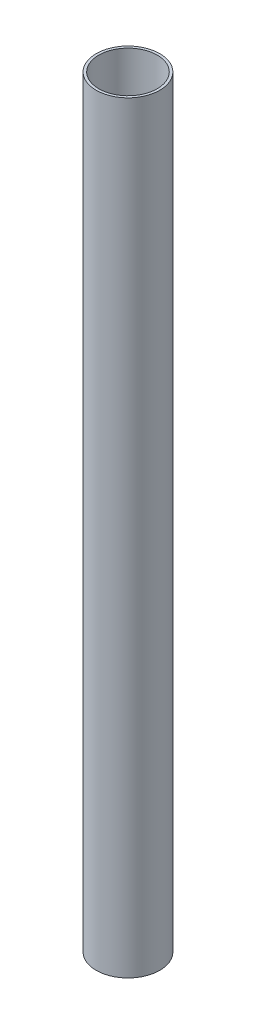
SolidWorks part; units mm, degrees
material "6061-T6 (SS)"
ref_plane "Front Plane" through (0, 0, 0) normal (0, 0, 1) x (1, 0, 0)
ref_plane "Top Plane" through (0, 0, 0) normal (0, 1, 0) x (1, 0, 0)
ref_plane "Right Plane" through (0, 0, 0) normal (1, 0, 0) x (0, 0, -1)
sketch "Sketch1" plane through (0, 0, 0) normal (0, 1, 0) x (1, 0, 0)
  circle A0 centre (0, 0) radius 38.1
  dimension "D1" = 76.2
extrude "Boss-Extrude1" add sketch "Sketch1" against normal blind 914.4
sketch "Sketch2" plane through (0, 0, 0) normal (0, 1, 0) x (1, 0, 0)
  circle A0 centre (0, 0) radius 35.052
  circle A1 centre (0, 0) radius 38.1 construction
  dimension "D1" = 3.048
extrude "Cut-Extrude1" cut sketch "Sketch2" against normal through all
